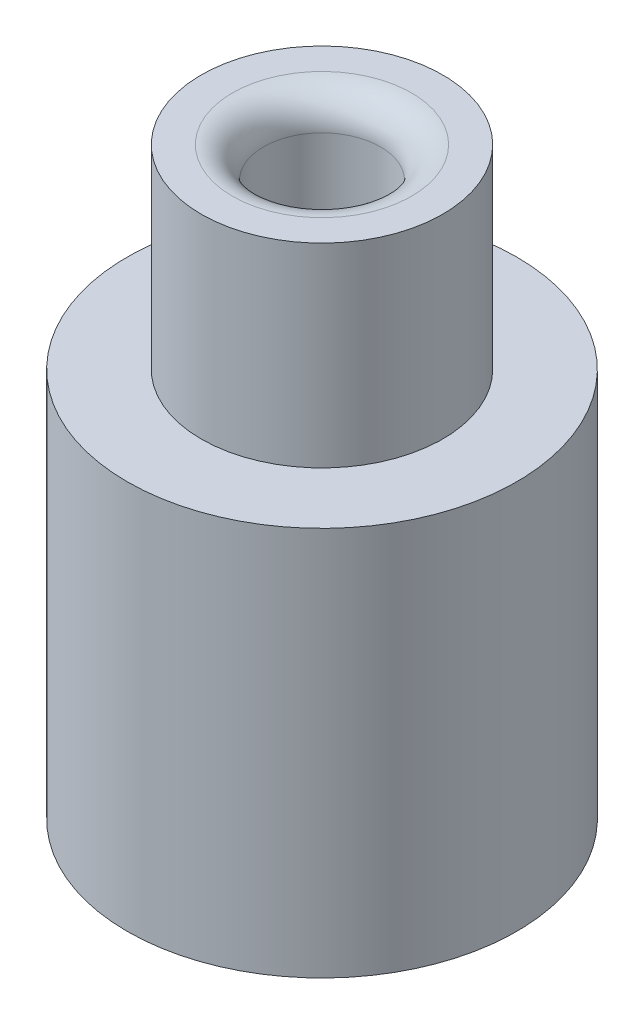
SolidWorks part; units mm, degrees
ref_plane "Front Plane" through (0, 0, 0) normal (0, 0, 1) x (1, 0, 0)
ref_plane "Top Plane" through (0, 0, 0) normal (0, 1, 0) x (1, 0, 0)
ref_plane "Right Plane" through (0, 0, 0) normal (1, 0, 0) x (0, 0, -1)
sketch "Esquisse1" plane through (0, 0, 0) normal (0, 1, 0) x (1, 0, 0)
  circle A0 centre (0, 0) radius 5
extrude "Boss.-Extru.1" add sketch "Esquisse1" along normal blind 6 and the other way blind 4
sketch "Esquisse2" plane through (0, 6, 0) normal (0, 1, 0) x (1, 0, 0)
  circle A0 centre (0, 0) radius 3.1
extrude "Boss.-Extru.2" add sketch "Esquisse2" along normal blind 5 and the other way blind 1
sketch "Esquisse3" plane through (0, 11, 0) normal (0, 1, 0) x (1, 0, 0)
  circle A0 centre (0, 0) radius 1.5
extrude "Enlèv. mat.-Extru.2" cut sketch "Esquisse3" against normal blind 10
sketch "Esquisse4" plane through (0, -4, 0) normal (0, -1, 0) x (1, 0, 0)
  circle A0 centre (0, 0) radius 2.25
extrude "Enlèv. mat.-Extru.3" cut sketch "Esquisse4" against normal blind 5
fillet "Congé1" radius 0.8 1 edges at (0, 11, 1.5)
